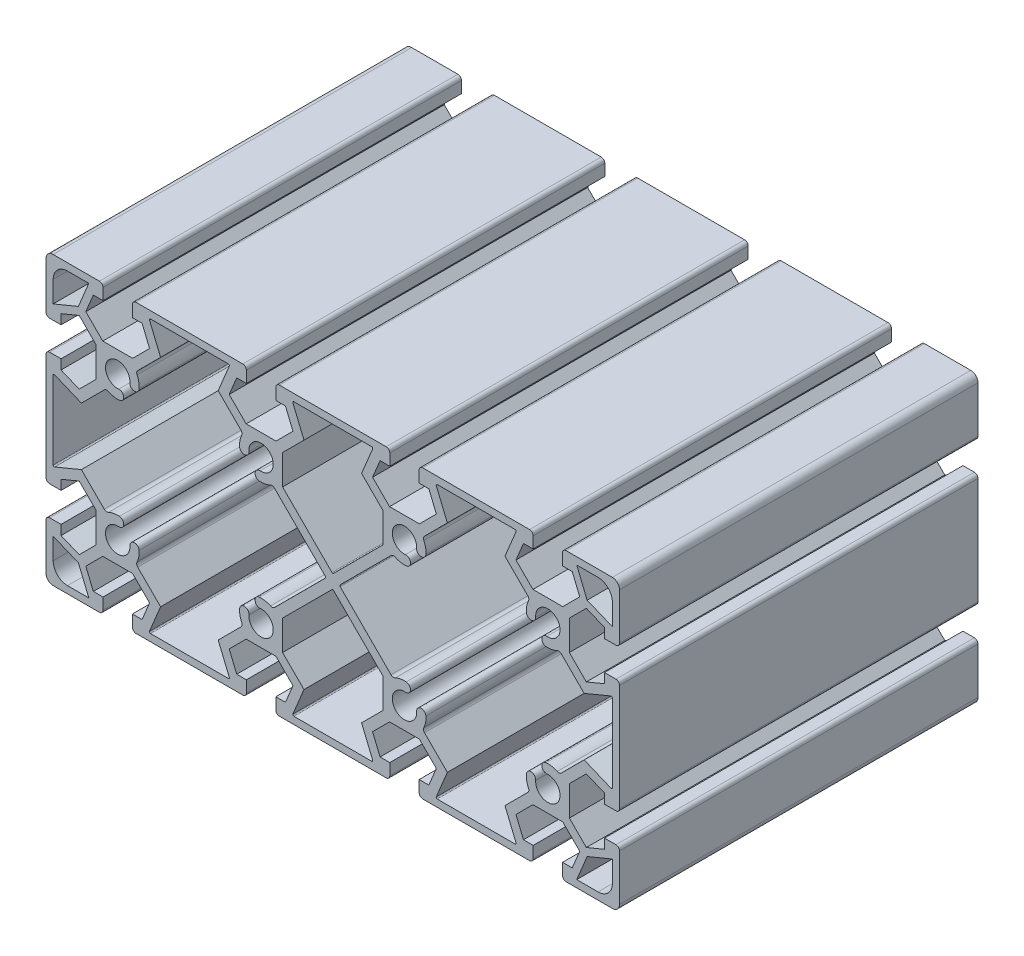
SolidWorks part; units mm, degrees
ref_plane "前视基准面" through (0, 0, 0) normal (0, 0, 1) x (1, 0, 0)
ref_plane "上视基准面" through (0, 0, 0) normal (0, 1, 0) x (1, 0, 0)
ref_plane "右视基准面" through (0, 0, 0) normal (1, 0, 0) x (0, 0, -1)
sketch "草图1" plane through (0, 0, 0) normal (0, 0, 1) x (1, 0, 0)
  line L0 (-38.9688, 40.1514) -> (-53.8688, 40.1514)
  line L1 (-64.0688, 40.1514) -> (-76.9688, 40.1514)
  line L2 (-67.0223, 38.1514) -> (-72.9688, 38.1514)
  line L3 (-52.1688, 35.9514) -> (-54.8688, 35.9514)
  line L4 (-63.0688, 35.9514) -> (-65.7688, 35.9514)
  line L5 (-78.9688, 38.1514) -> (-78.9688, 25.2514)
  line L6 (-76.9688, 34.1514) -> (-76.9688, 28.2049)
  line L7 (-78.9688, 15.0514) -> (-78.9688, 0.1514)
  line L8 (-76.9688, 10.9995) -> (-76.9688, 0.1514)
  line L9 (-69.7048, 29.049) -> (-64.9688, 24.3129)
  line L10 (-67.8663, 30.8874) -> (-63.1303, 26.1514)
  line L11 (-63.1303, 26.1514) -> (-54.8073, 26.1514)
  line L12 (-64.9688, 24.3129) -> (-64.9688, 15.9899)
  line L13 (-54.8688, 39.1514) -> (-54.8688, 35.9514)
  line L14 (-63.0688, 39.1514) -> (-63.0688, 35.9514)
  line L15 (-77.9688, 24.2514) -> (-74.7688, 24.2514)
  line L16 (-74.7688, 24.2514) -> (-74.7688, 26.9514)
  line L17 (-67.8663, 30.8874) -> (-65.7688, 35.9514)
  line L18 (-69.9356, 31.1182) -> (-67.0223, 38.1514)
  line L19 (-69.7048, 29.049) -> (-74.7688, 26.9514)
  line L20 (-69.9356, 31.1182) -> (-76.9688, 28.2049)
  line L21 (-69.7048, 11.2538) -> (-64.9688, 15.9899)
  line L22 (-69.0948, 8.1869) -> (-62.7245, 14.5572)
  line L23 (-77.9688, 16.0514) -> (-74.7688, 16.0514)
  line L24 (-74.7688, 16.0514) -> (-74.7688, 13.3514)
  line L25 (-69.7048, 11.2538) -> (-74.7688, 13.3514)
  line L26 (-69.0948, 8.1869) -> (-76.554, 11.2766)
  line L28 (-50.0712, 30.8874) -> (-54.8073, 26.1514)
  line L29 (-50.0712, 30.8874) -> (-52.1688, 35.9514)
  line L30 (-47.0043, 30.2774) -> (-53.3746, 23.9071)
  line L31 (-47.0043, 30.2774) -> (-50.094, 37.7366)
  line L32 (-49.8169, 38.1514) -> (-38.9688, 38.1514)
  line L33 (41.0312, 40.1514) -> (55.9312, 40.1514)
  line L34 (66.1312, 40.1514) -> (79.0312, 40.1514)
  line L35 (69.0847, 38.1514) -> (75.0312, 38.1514)
  line L36 (54.2312, 35.9514) -> (56.9312, 35.9514)
  line L37 (65.1312, 35.9514) -> (67.8312, 35.9514)
  line L38 (81.0312, 38.1514) -> (81.0312, 25.2514)
  line L39 (79.0312, 34.1514) -> (79.0312, 28.2049)
  line L40 (81.0312, 15.0514) -> (81.0312, 0.1514)
  line L41 (79.0312, 10.9995) -> (79.0312, 0.1514)
  line L42 (71.7673, 29.049) -> (67.0312, 24.3129)
  line L43 (69.9288, 30.8874) -> (65.1927, 26.1514)
  line L44 (65.1927, 26.1514) -> (56.8697, 26.1514)
  line L45 (67.0312, 24.3129) -> (67.0312, 15.9899)
  line L46 (56.9312, 39.1514) -> (56.9312, 35.9514)
  line L47 (65.1312, 39.1514) -> (65.1312, 35.9514)
  line L48 (80.0312, 24.2514) -> (76.8312, 24.2514)
  line L49 (76.8312, 24.2514) -> (76.8312, 26.9514)
  line L50 (69.9288, 30.8874) -> (67.8312, 35.9514)
  line L51 (71.998, 31.1182) -> (69.0847, 38.1514)
  line L52 (71.7673, 29.049) -> (76.8312, 26.9514)
  line L53 (71.998, 31.1182) -> (79.0312, 28.2049)
  line L54 (71.7673, 11.2538) -> (67.0312, 15.9899)
  line L55 (71.1572, 8.1869) -> (64.7869, 14.5572)
  line L56 (80.0312, 16.0514) -> (76.8312, 16.0514)
  line L57 (76.8312, 16.0514) -> (76.8312, 13.3514)
  line L58 (71.7673, 11.2538) -> (76.8312, 13.3514)
  line L59 (71.1572, 8.1869) -> (78.6164, 11.2766)
  line L61 (52.1337, 30.8874) -> (56.8697, 26.1514)
  line L62 (52.1337, 30.8874) -> (54.2312, 35.9514)
  line L63 (49.0667, 30.2774) -> (55.437, 23.9071)
  line L64 (49.0667, 30.2774) -> (52.1564, 37.7366)
  line L65 (51.8793, 38.1514) -> (41.0312, 38.1514)
  line L66 (-38.9688, -39.8486) -> (-53.8688, -39.8486)
  line L67 (-64.0688, -39.8486) -> (-76.9688, -39.8486)
  line L68 (-67.0223, -37.8486) -> (-72.9688, -37.8486)
  line L69 (-52.1688, -35.6486) -> (-54.8688, -35.6486)
  line L70 (-63.0688, -35.6486) -> (-65.7688, -35.6486)
  line L71 (-78.9688, -37.8486) -> (-78.9688, -24.9486)
  line L72 (-76.9688, -33.8486) -> (-76.9688, -27.9021)
  line L73 (-78.9688, -14.7486) -> (-78.9688, 0.1514)
  line L74 (-76.9688, -10.6967) -> (-76.9688, 0.1514)
  line L75 (-69.7048, -28.7462) -> (-64.9688, -24.0101)
  line L76 (-67.8663, -30.5846) -> (-63.1303, -25.8486)
  line L77 (-63.1303, -25.8486) -> (-54.8073, -25.8486)
  line L78 (-64.9688, -24.0101) -> (-64.9688, -15.6871)
  line L79 (-54.8688, -38.8486) -> (-54.8688, -35.6486)
  line L80 (-63.0688, -38.8486) -> (-63.0688, -35.6486)
  line L81 (-77.9688, -23.9486) -> (-74.7688, -23.9486)
  line L82 (-74.7688, -23.9486) -> (-74.7688, -26.6486)
  line L83 (-67.8663, -30.5846) -> (-65.7688, -35.6486)
  line L84 (-69.9356, -30.8154) -> (-67.0223, -37.8486)
  line L85 (-69.7048, -28.7462) -> (-74.7688, -26.6486)
  line L86 (-69.9356, -30.8154) -> (-76.9688, -27.9021)
  line L87 (-69.7048, -10.951) -> (-64.9688, -15.6871)
  line L88 (-69.0948, -7.8841) -> (-62.7245, -14.2544)
  line L89 (-77.9688, -15.7486) -> (-74.7688, -15.7486)
  line L90 (-74.7688, -15.7486) -> (-74.7688, -13.0486)
  line L91 (-69.7048, -10.951) -> (-74.7688, -13.0486)
  line L92 (-69.0948, -7.8841) -> (-76.554, -10.9738)
  line L94 (-50.0712, -30.5846) -> (-54.8073, -25.8486)
  line L95 (-50.0712, -30.5846) -> (-52.1688, -35.6486)
  line L96 (-47.0043, -29.9746) -> (-53.3746, -23.6043)
  line L97 (-47.0043, -29.9746) -> (-50.094, -37.4338)
  line L98 (41.0312, -39.8486) -> (55.9312, -39.8486)
  line L99 (66.1312, -39.8486) -> (79.0312, -39.8486)
  line L100 (69.0847, -37.8486) -> (75.0312, -37.8486)
  line L101 (54.2312, -35.6486) -> (56.9312, -35.6486)
  line L102 (65.1312, -35.6486) -> (67.8312, -35.6486)
  line L103 (81.0312, -37.8486) -> (81.0312, -24.9486)
  line L104 (79.0312, -33.8486) -> (79.0312, -27.9021)
  line L105 (81.0312, -14.7486) -> (81.0312, 0.1514)
  line L106 (79.0312, -10.6967) -> (79.0312, 0.1514)
  line L107 (71.7673, -28.7462) -> (67.0312, -24.0101)
  line L108 (69.9288, -30.5846) -> (65.1927, -25.8486)
  line L109 (65.1927, -25.8486) -> (56.8697, -25.8486)
  line L110 (67.0312, -24.0101) -> (67.0312, -15.6871)
  line L111 (56.9312, -38.8486) -> (56.9312, -35.6486)
  line L112 (65.1312, -38.8486) -> (65.1312, -35.6486)
  line L113 (80.0312, -23.9486) -> (76.8312, -23.9486)
  line L114 (76.8312, -23.9486) -> (76.8312, -26.6486)
  line L115 (69.9288, -30.5846) -> (67.8312, -35.6486)
  line L116 (71.998, -30.8154) -> (69.0847, -37.8486)
  line L117 (71.7673, -28.7462) -> (76.8312, -26.6486)
  line L118 (71.998, -30.8154) -> (79.0312, -27.9021)
  line L119 (71.7673, -10.951) -> (67.0312, -15.6871)
  line L120 (71.1572, -7.8841) -> (64.7869, -14.2544)
  line L121 (80.0312, -15.7486) -> (76.8312, -15.7486)
  line L122 (76.8312, -15.7486) -> (76.8312, -13.0486)
  line L123 (71.7673, -10.951) -> (76.8312, -13.0486)
  line L124 (71.1572, -7.8841) -> (78.6164, -10.9738)
  line L126 (52.1337, -30.5846) -> (56.8697, -25.8486)
  line L127 (52.1337, -30.5846) -> (54.2312, -35.6486)
  line L128 (49.0667, -29.9746) -> (55.437, -23.6043)
  line L129 (49.0667, -29.9746) -> (52.1564, -37.4338)
  line L130 (51.8793, -37.8486) -> (41.0312, -37.8486)
  line L131 (-49.8169, -37.8486) -> (-38.9688, -37.8486)
  line L132 (-38.9688, 40.1514) -> (-24.0688, 40.1514)
  line L133 (-25.7688, 35.9514) -> (-23.0688, 35.9514)
  line L134 (-14.8073, 26.1514) -> (-23.1303, 26.1514)
  line L135 (-12.9688, 24.3129) -> (-12.9688, 15.9899)
  line L136 (-23.0688, 39.1514) -> (-23.0688, 35.9514)
  line L138 (-27.8663, 30.8874) -> (-23.1303, 26.1514)
  line L139 (-27.8663, 30.8874) -> (-25.7688, 35.9514)
  line L140 (-30.9333, 30.2774) -> (-24.563, 23.9071)
  line L141 (-30.9333, 30.2774) -> (-27.8436, 37.7366)
  line L142 (-28.1207, 38.1514) -> (-38.9688, 38.1514)
  line L143 (-38.9688, -39.8486) -> (-24.0688, -39.8486)
  line L144 (-25.7688, -35.6486) -> (-23.0688, -35.6486)
  line L145 (-14.8073, -25.8486) -> (-23.1303, -25.8486)
  line L146 (-12.9688, -24.0101) -> (-12.9688, -15.6871)
  line L147 (-23.0688, -38.8486) -> (-23.0688, -35.6486)
  line L149 (-27.8663, -30.5846) -> (-23.1303, -25.8486)
  line L150 (-27.8663, -30.5846) -> (-25.7688, -35.6486)
  line L151 (-30.9333, -29.9746) -> (-24.563, -23.6043)
  line L152 (-30.9333, -29.9746) -> (-27.8436, -37.4338)
  line L153 (-28.1207, -37.8486) -> (-38.9688, -37.8486)
  line L154 (41.0312, 40.1514) -> (26.1312, 40.1514)
  line L155 (27.8312, 35.9514) -> (25.1312, 35.9514)
  line L156 (16.8697, 26.1514) -> (25.1927, 26.1514)
  line L157 (15.0312, 24.3129) -> (15.0312, 15.9899)
  line L158 (25.1312, 39.1514) -> (25.1312, 35.9514)
  line L160 (29.9288, 30.8874) -> (25.1927, 26.1514)
  line L161 (29.9288, 30.8874) -> (27.8312, 35.9514)
  line L162 (32.9957, 30.2774) -> (26.6254, 23.9071)
  line L163 (32.9957, 30.2774) -> (29.906, 37.7366)
  line L164 (30.1831, 38.1514) -> (41.0312, 38.1514)
  line L165 (41.0312, -39.8486) -> (26.1312, -39.8486)
  line L166 (27.8312, -35.6486) -> (25.1312, -35.6486)
  line L167 (16.8697, -25.8486) -> (25.1927, -25.8486)
  line L168 (15.0312, -24.0101) -> (15.0312, -15.6871)
  line L169 (25.1312, -38.8486) -> (25.1312, -35.6486)
  line L171 (29.9288, -30.5846) -> (25.1927, -25.8486)
  line L172 (29.9288, -30.5846) -> (27.8312, -35.6486)
  line L173 (32.9957, -29.9746) -> (26.6254, -23.6043)
  line L174 (32.9957, -29.9746) -> (29.906, -37.4338)
  line L175 (30.1831, -37.8486) -> (41.0312, -37.8486)
  line L176 (1.0312, 40.1514) -> (-13.8688, 40.1514)
  line L177 (-12.1688, 35.9514) -> (-14.8688, 35.9514)
  line L178 (-14.8688, 39.1514) -> (-14.8688, 35.9514)
  line L180 (-10.0712, 30.8874) -> (-14.8073, 26.1514)
  line L181 (-10.0712, 30.8874) -> (-12.1688, 35.9514)
  line L182 (-7.0043, 30.2774) -> (-12.9688, 24.3129)
  line L183 (-7.0043, 30.2774) -> (-10.094, 37.7366)
  line L184 (-9.8169, 38.1514) -> (1.0312, 38.1514)
  line L185 (1.0312, 40.1514) -> (15.9312, 40.1514)
  line L186 (14.2312, 35.9514) -> (16.9312, 35.9514)
  line L187 (16.9312, 39.1514) -> (16.9312, 35.9514)
  line L189 (12.1337, 30.8874) -> (16.8697, 26.1514)
  line L190 (12.1337, 30.8874) -> (14.2312, 35.9514)
  line L191 (9.0667, 30.2774) -> (15.0312, 24.3129)
  line L192 (9.0667, 30.2774) -> (12.1564, 37.7366)
  line L193 (11.8793, 38.1514) -> (1.0312, 38.1514)
  line L194 (1.0312, -39.8486) -> (-13.8688, -39.8486)
  line L195 (-12.1688, -35.6486) -> (-14.8688, -35.6486)
  line L196 (-14.8688, -38.8486) -> (-14.8688, -35.6486)
  line L198 (-10.0712, -30.5846) -> (-14.8073, -25.8486)
  line L199 (-10.0712, -30.5846) -> (-12.1688, -35.6486)
  line L200 (-7.0043, -29.9746) -> (-12.9688, -24.0101)
  line L201 (-7.0043, -29.9746) -> (-10.094, -37.4338)
  line L202 (-9.8169, -37.8486) -> (1.0312, -37.8486)
  line L203 (1.0312, -39.8486) -> (15.9312, -39.8486)
  line L204 (14.2312, -35.6486) -> (16.9312, -35.6486)
  line L205 (16.9312, -38.8486) -> (16.9312, -35.6486)
  line L207 (12.1337, -30.5846) -> (16.8697, -25.8486)
  line L208 (12.1337, -30.5846) -> (14.2312, -35.6486)
  line L209 (9.0667, -29.9746) -> (15.0312, -24.0101)
  line L210 (9.0667, -29.9746) -> (12.1564, -37.4338)
  line L211 (11.8793, -37.8486) -> (1.0312, -37.8486)
  line L212 (-15.2131, 14.5572) -> (-1.0194, 0.3635)
  line L213 (1.2433, -1.8992) -> (15.0312, -15.6871)
  line L214 (-12.9688, 15.9899) -> (0.8191, 2.202)
  line L215 (3.0818, -0.0607) -> (17.2755, -14.2544)
  line L216 (17.2755, 14.5572) -> (3.0818, 0.3635)
  line L217 (0.8191, -1.8992) -> (-12.9688, -15.6871)
  line L218 (15.0312, 15.9899) -> (1.2433, 2.202)
  line L219 (-1.0194, -0.0607) -> (-15.2131, -14.2544)
  arc A0 (-53.8688, 40.1514) -> (-54.8688, 39.1514) centre (-53.8688, 39.1514) ccw
  arc A1 (-76.9688, 40.1514) -> (-78.9688, 38.1514) centre (-76.9688, 38.1514) ccw
  arc A2 (-72.9688, 38.1514) -> (-76.9688, 34.1514) centre (-72.9688, 34.1514) ccw
  arc A3 (-78.9688, 25.2514) -> (-77.9688, 24.2514) centre (-77.9688, 25.2514) ccw
  arc A4 (-55.5801, 19.874) -> (-58.6914, 16.7627) centre (-58.9688, 20.1514) ccw
  arc A5 (-63.0688, 39.1514) -> (-64.0688, 40.1514) centre (-64.0688, 39.1514) ccw
  arc A6 (-77.9688, 16.0514) -> (-78.9688, 15.0514) centre (-77.9688, 15.0514) ccw
  arc A7 (-76.554, 11.2766) -> (-76.9688, 10.9995) centre (-76.6688, 10.9995) ccw
  arc A8 (-61.5819, 14.7503) -> (-58.4793, 14.1714) centre (-58.9688, 20.1514) ccw
  arc A9 (-52.9888, 19.6619) -> (-53.5677, 22.7645) centre (-58.9688, 20.1514) ccw
  arc A10 (-61.5819, 14.7503) -> (-62.7245, 14.5572) centre (-62.0174, 13.8501) ccw
  arc A11 (-53.3746, 23.9071) -> (-53.5677, 22.7645) centre (-52.6675, 23.2) ccw
  arc A12 (-49.8169, 38.1514) -> (-50.094, 37.7366) centre (-49.8169, 37.8514) ccw
  arc A13 (-58.4793, 14.1714) -> (-58.6914, 16.7627) centre (-58.5853, 15.4671) ccw
  arc A14 (-55.5801, 19.874) -> (-52.9888, 19.6619) centre (-54.2845, 19.7679) ccw
  arc A15 (56.9312, 39.1514) -> (55.9312, 40.1514) centre (55.9312, 39.1514) ccw
  arc A16 (81.0312, 38.1514) -> (79.0312, 40.1514) centre (79.0312, 38.1514) ccw
  arc A17 (79.0312, 34.1514) -> (75.0312, 38.1514) centre (75.0312, 34.1514) ccw
  arc A18 (80.0312, 24.2514) -> (81.0312, 25.2514) centre (80.0312, 25.2514) ccw
  arc A19 (60.7538, 16.7627) -> (57.6426, 19.874) centre (61.0312, 20.1514) ccw
  arc A20 (66.1312, 40.1514) -> (65.1312, 39.1514) centre (66.1312, 39.1514) ccw
  arc A21 (81.0312, 15.0514) -> (80.0312, 16.0514) centre (80.0312, 15.0514) ccw
  arc A22 (79.0312, 10.9995) -> (78.6164, 11.2766) centre (78.7312, 10.9995) ccw
  arc A23 (60.5417, 14.1714) -> (63.6443, 14.7503) centre (61.0312, 20.1514) ccw
  arc A24 (55.6301, 22.7645) -> (55.0512, 19.6619) centre (61.0312, 20.1514) ccw
  arc A25 (64.7869, 14.5572) -> (63.6443, 14.7503) centre (64.0798, 13.8501) ccw
  arc A26 (55.6301, 22.7645) -> (55.437, 23.9071) centre (54.7299, 23.2) ccw
  arc A27 (52.1564, 37.7366) -> (51.8793, 38.1514) centre (51.8793, 37.8514) ccw
  arc A28 (60.7538, 16.7627) -> (60.5417, 14.1714) centre (60.6478, 15.4671) ccw
  arc A29 (55.0512, 19.6619) -> (57.6426, 19.874) centre (56.3469, 19.7679) ccw
  arc A30 (-54.8688, -38.8486) -> (-53.8688, -39.8486) centre (-53.8688, -38.8486) ccw
  arc A31 (-78.9688, -37.8486) -> (-76.9688, -39.8486) centre (-76.9688, -37.8486) ccw
  arc A32 (-76.9688, -33.8486) -> (-72.9688, -37.8486) centre (-72.9688, -33.8486) ccw
  arc A33 (-77.9688, -23.9486) -> (-78.9688, -24.9486) centre (-77.9688, -24.9486) ccw
  arc A34 (-58.6914, -16.4599) -> (-55.5801, -19.5712) centre (-58.9688, -19.8486) ccw
  arc A35 (-64.0688, -39.8486) -> (-63.0688, -38.8486) centre (-64.0688, -38.8486) ccw
  arc A36 (-78.9688, -14.7486) -> (-77.9688, -15.7486) centre (-77.9688, -14.7486) ccw
  arc A37 (-76.9688, -10.6967) -> (-76.554, -10.9738) centre (-76.6688, -10.6967) ccw
  arc A38 (-58.4793, -13.8686) -> (-61.5819, -14.4475) centre (-58.9688, -19.8486) ccw
  arc A39 (-53.5677, -22.4617) -> (-52.9888, -19.3591) centre (-58.9688, -19.8486) ccw
  arc A40 (-62.7245, -14.2544) -> (-61.5819, -14.4475) centre (-62.0174, -13.5473) ccw
  arc A41 (-53.5677, -22.4617) -> (-53.3746, -23.6043) centre (-52.6675, -22.8972) ccw
  arc A42 (-50.094, -37.4338) -> (-49.8169, -37.8486) centre (-49.8169, -37.5486) ccw
  arc A43 (-58.6914, -16.4599) -> (-58.4793, -13.8686) centre (-58.5853, -15.1643) ccw
  arc A44 (-52.9888, -19.3591) -> (-55.5801, -19.5712) centre (-54.2845, -19.4651) ccw
  arc A45 (55.9312, -39.8486) -> (56.9312, -38.8486) centre (55.9312, -38.8486) ccw
  arc A46 (79.0312, -39.8486) -> (81.0312, -37.8486) centre (79.0312, -37.8486) ccw
  arc A47 (75.0312, -37.8486) -> (79.0312, -33.8486) centre (75.0312, -33.8486) ccw
  arc A48 (81.0312, -24.9486) -> (80.0312, -23.9486) centre (80.0312, -24.9486) ccw
  arc A49 (57.6426, -19.5712) -> (60.7538, -16.4599) centre (61.0312, -19.8486) ccw
  arc A50 (65.1312, -38.8486) -> (66.1312, -39.8486) centre (66.1312, -38.8486) ccw
  arc A51 (80.0312, -15.7486) -> (81.0312, -14.7486) centre (80.0312, -14.7486) ccw
  arc A52 (78.6164, -10.9738) -> (79.0312, -10.6967) centre (78.7312, -10.6967) ccw
  arc A53 (63.6443, -14.4475) -> (60.5417, -13.8686) centre (61.0312, -19.8486) ccw
  arc A54 (55.0512, -19.3591) -> (55.6301, -22.4617) centre (61.0312, -19.8486) ccw
  arc A55 (63.6443, -14.4475) -> (64.7869, -14.2544) centre (64.0798, -13.5473) ccw
  arc A56 (55.437, -23.6043) -> (55.6301, -22.4617) centre (54.7299, -22.8972) ccw
  arc A57 (51.8793, -37.8486) -> (52.1564, -37.4338) centre (51.8793, -37.5486) ccw
  arc A58 (60.5417, -13.8686) -> (60.7538, -16.4599) centre (60.6478, -15.1643) ccw
  arc A59 (57.6426, -19.5712) -> (55.0512, -19.3591) centre (56.3469, -19.4651) ccw
  arc A60 (-23.0688, 39.1514) -> (-24.0688, 40.1514) centre (-24.0688, 39.1514) ccw
  arc A61 (-19.2462, 16.7627) -> (-22.3574, 19.874) centre (-18.9688, 20.1514) ccw
  arc A62 (-19.4583, 14.1714) -> (-16.3557, 14.7503) centre (-18.9688, 20.1514) ccw
  arc A63 (-24.3699, 22.7645) -> (-24.9488, 19.6619) centre (-18.9688, 20.1514) ccw
  arc A64 (-15.2131, 14.5572) -> (-16.3557, 14.7503) centre (-15.9202, 13.8501) ccw
  arc A65 (-24.3699, 22.7645) -> (-24.563, 23.9071) centre (-25.2701, 23.2) ccw
  arc A66 (-27.8436, 37.7366) -> (-28.1207, 38.1514) centre (-28.1207, 37.8514) ccw
  arc A67 (-19.2462, 16.7627) -> (-19.4583, 14.1714) centre (-19.3522, 15.4671) ccw
  arc A68 (-24.9488, 19.6619) -> (-22.3574, 19.874) centre (-23.6531, 19.7679) ccw
  arc A69 (-24.0688, -39.8486) -> (-23.0688, -38.8486) centre (-24.0688, -38.8486) ccw
  arc A70 (-22.3574, -19.5712) -> (-19.2462, -16.4599) centre (-18.9688, -19.8486) ccw
  arc A71 (-16.3557, -14.4475) -> (-19.4583, -13.8686) centre (-18.9688, -19.8486) ccw
  arc A72 (-24.9488, -19.3591) -> (-24.3699, -22.4617) centre (-18.9688, -19.8486) ccw
  arc A73 (-16.3557, -14.4475) -> (-15.2131, -14.2544) centre (-15.9202, -13.5473) ccw
  arc A74 (-24.563, -23.6043) -> (-24.3699, -22.4617) centre (-25.2701, -22.8972) ccw
  arc A75 (-28.1207, -37.8486) -> (-27.8436, -37.4338) centre (-28.1207, -37.5486) ccw
  arc A76 (-19.4583, -13.8686) -> (-19.2462, -16.4599) centre (-19.3522, -15.1643) ccw
  arc A77 (-22.3574, -19.5712) -> (-24.9488, -19.3591) centre (-23.6531, -19.4651) ccw
  arc A78 (26.1312, 40.1514) -> (25.1312, 39.1514) centre (26.1312, 39.1514) ccw
  arc A79 (24.4199, 19.874) -> (21.3086, 16.7627) centre (21.0312, 20.1514) ccw
  arc A80 (18.4181, 14.7503) -> (21.5207, 14.1714) centre (21.0312, 20.1514) ccw
  arc A81 (27.0112, 19.6619) -> (26.4323, 22.7645) centre (21.0312, 20.1514) ccw
  arc A82 (18.4181, 14.7503) -> (17.2755, 14.5572) centre (17.9826, 13.8501) ccw
  arc A83 (26.6254, 23.9071) -> (26.4323, 22.7645) centre (27.3325, 23.2) ccw
  arc A84 (30.1831, 38.1514) -> (29.906, 37.7366) centre (30.1831, 37.8514) ccw
  arc A85 (21.5207, 14.1714) -> (21.3086, 16.7627) centre (21.4147, 15.4671) ccw
  arc A86 (24.4199, 19.874) -> (27.0112, 19.6619) centre (25.7155, 19.7679) ccw
  arc A87 (25.1312, -38.8486) -> (26.1312, -39.8486) centre (26.1312, -38.8486) ccw
  arc A88 (21.3086, -16.4599) -> (24.4199, -19.5712) centre (21.0312, -19.8486) ccw
  arc A89 (21.5207, -13.8686) -> (18.4181, -14.4475) centre (21.0312, -19.8486) ccw
  arc A90 (26.4323, -22.4617) -> (27.0112, -19.3591) centre (21.0312, -19.8486) ccw
  arc A91 (17.2755, -14.2544) -> (18.4181, -14.4475) centre (17.9826, -13.5473) ccw
  arc A92 (26.4323, -22.4617) -> (26.6254, -23.6043) centre (27.3325, -22.8972) ccw
  arc A93 (29.906, -37.4338) -> (30.1831, -37.8486) centre (30.1831, -37.5486) ccw
  arc A94 (21.3086, -16.4599) -> (21.5207, -13.8686) centre (21.4147, -15.1643) ccw
  arc A95 (27.0112, -19.3591) -> (24.4199, -19.5712) centre (25.7155, -19.4651) ccw
  arc A96 (-13.8688, 40.1514) -> (-14.8688, 39.1514) centre (-13.8688, 39.1514) ccw
  arc A97 (-9.8169, 38.1514) -> (-10.094, 37.7366) centre (-9.8169, 37.8514) ccw
  arc A98 (16.9312, 39.1514) -> (15.9312, 40.1514) centre (15.9312, 39.1514) ccw
  arc A99 (12.1564, 37.7366) -> (11.8793, 38.1514) centre (11.8793, 37.8514) ccw
  arc A100 (-14.8688, -38.8486) -> (-13.8688, -39.8486) centre (-13.8688, -38.8486) ccw
  arc A101 (-10.094, -37.4338) -> (-9.8169, -37.8486) centre (-9.8169, -37.5486) ccw
  arc A102 (15.9312, -39.8486) -> (16.9312, -38.8486) centre (15.9312, -38.8486) ccw
  arc A103 (11.8793, -37.8486) -> (12.1564, -37.4338) centre (11.8793, -37.5486) ccw
  arc A104 (-1.0194, -0.0607) -> (-1.0194, 0.3635) centre (-1.2315, 0.1514) ccw
  arc A105 (0.8191, 2.202) -> (1.2433, 2.202) centre (1.0312, 2.4141) ccw
  arc A106 (3.0818, 0.3635) -> (3.0818, -0.0607) centre (3.294, 0.1514) ccw
  arc A107 (1.2433, -1.8992) -> (0.8191, -1.8992) centre (1.0312, -2.1113) ccw
extrude "凸台-拉伸1" add sketch "草图1" along normal blind 100
